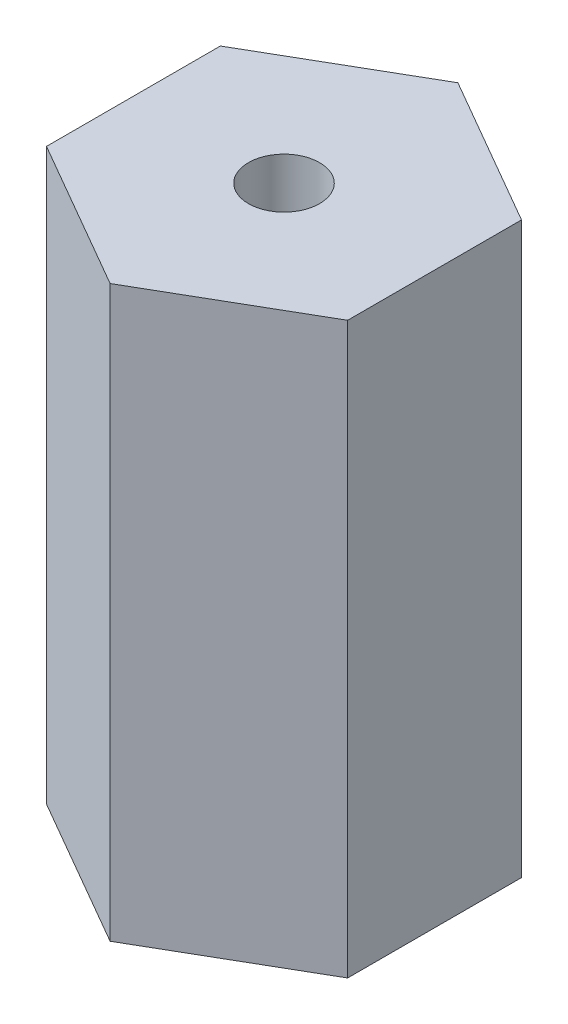
SolidWorks part; units mm, degrees
material "6061-T6 (SS)"
ref_plane "Front Plane" through (0, 0, 0) normal (0, 0, 1) x (1, 0, 0)
ref_plane "Top Plane" through (0, 0, 0) normal (0, 1, 0) x (1, 0, 0)
ref_plane "Right Plane" through (0, 0, 0) normal (1, 0, 0) x (0, 0, -1)
sketch "Sketch1" plane through (0, 0, 0) normal (0, 1, 0) x (1, 0, 0)
  line L0 (0, 0) -> (0, 12337.41) construction
  line L8 (0, 7.3323) -> (-6.35, 3.6662)
  line L9 (-6.35, 3.6662) -> (-6.35, -3.6662)
  line L10 (-6.35, -3.6662) -> (0, -7.3323)
  line L11 (0, -7.3323) -> (6.35, -3.6662)
  line L12 (6.35, -3.6662) -> (6.35, 3.6662)
  line L13 (6.35, 3.6662) -> (0, 7.3323)
  circle A0 centre (0, 0) radius 6.35 construction
  circle A1 centre (0, 0) radius 1.5
  dimension "D2" = 3
  dimension "D1" = 12.7
extrude "Boss-Extrude1" add sketch "Sketch1" along normal blind 24.0204
sketch "Sketch2" plane through (0, 0, 0) normal (0, 1, 0) x (1, 0, 0)
  circle A0 centre (0, 0) radius 5
  dimension "D1" = 10
extrude "Cut-Extrude1" cut sketch "Sketch2" along normal blind 2.54
